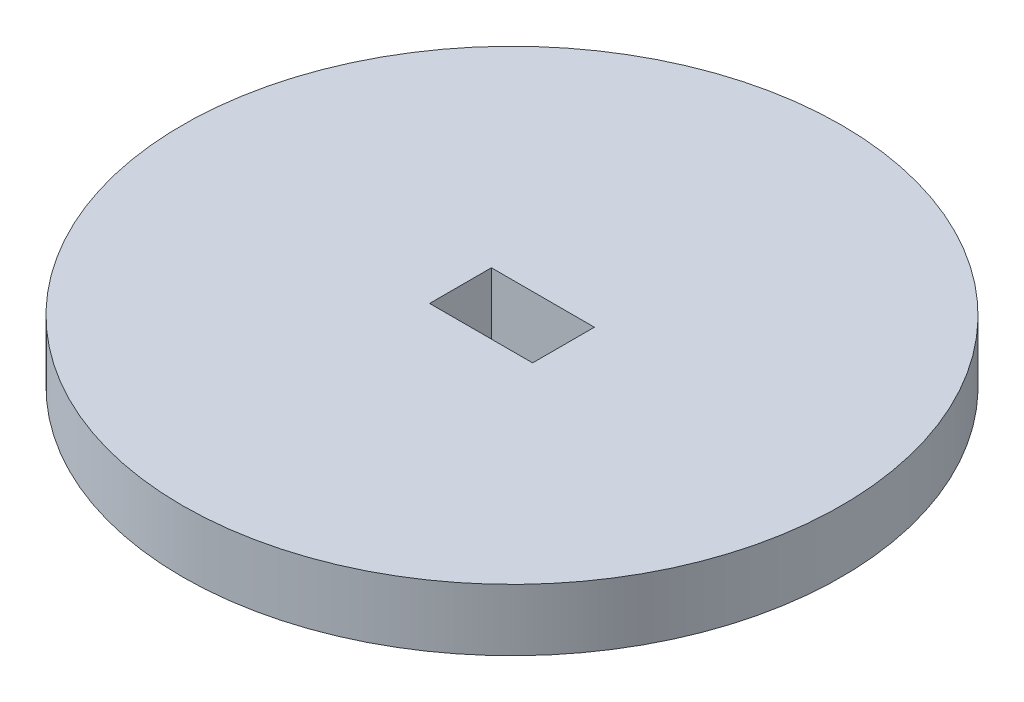
SolidWorks part; units mm, degrees
ref_plane "Plano frontal" through (0, 0, 0) normal (0, 0, 1) x (1, 0, 0)
ref_plane "Plano superior" through (0, 0, 0) normal (0, 1, 0) x (1, 0, 0)
ref_plane "Plano direito" through (0, 0, 0) normal (1, 0, 0) x (0, 0, -1)
sketch "Esboço1" plane through (0, 0, 0) normal (0, 1, 0) x (1, 0, 0)
  circle A0 centre (0, 0) radius 32
  dimension "D1" = 64
extrude "Ressalto-extrusão1" add sketch "Esboço1" along normal blind 6
sketch "Esboço2" plane through (0, 6, 0) normal (0, 1, 0) x (1, 0, 0)
  line L1 (5, -3) -> (-5, -3)
  line L2 (5, -3) -> (5, 3)
  line L3 (5, 3) -> (-5, 3)
  line L4 (-5, -3) -> (-5, 3)
  line L5 (5, -3) -> (-5, 3) construction
  line L6 (5, 3) -> (-5, -3) construction
  point P0 (0, 0)
  dimension "D1" = 10
  dimension "D2" = 6
extrude "Corte-extrusão1" cut sketch "Esboço2" against normal blind 6
